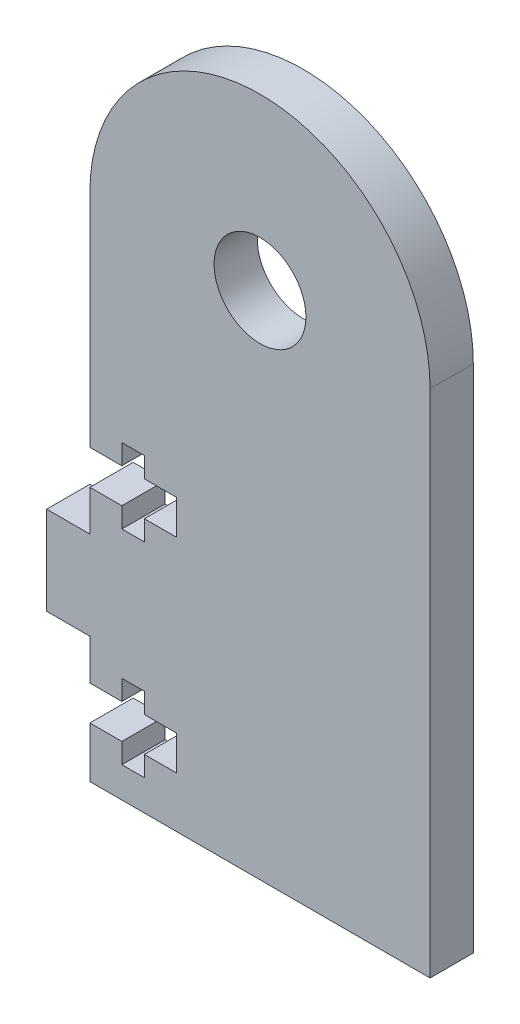
SolidWorks part; units mm, degrees
ref_plane "Front Plane" through (0, 0, 0) normal (0, 0, 1) x (1, 0, 0)
ref_plane "Top Plane" through (0, 0, 0) normal (0, 1, 0) x (1, 0, 0)
ref_plane "Right Plane" through (0, 0, 0) normal (1, 0, 0) x (0, 0, -1)
sketch "Sketch2" plane through (0, 0, 0) normal (0, 0, 1) x (1, 0, 0)
  line L0 (-25, 0) -> (25, 0) construction
  line L2 (-25, 0) -> (-25, -75)
  line L3 (-25, -75) -> (25, -75)
  line L4 (25, 0) -> (25, -75)
  arc A0 (25, 0) -> (-25, 0) centre (0, 0) ccw
  dimension "D1" = 50
  dimension "D2" = 75
extrude "Boss-Extrude1" add sketch "Sketch2" along normal blind 6.35
sketch "Sketch3" plane through (0, 0, 6.35) normal (0, 0, 1) x (1, 0, 0)
  line L0 (-25, -65) -> (-12.3, -65) construction
  line L1 (-12.3, -67.54) -> (-16.999, -67.54)
  line L2 (-25, -67.54) -> (-25, -62.46)
  line L3 (-12.3, -62.46) -> (-16.999, -62.46)
  line L4 (-20.301, -67.54) -> (-25, -67.54)
  line L5 (-20.301, -70.4991) -> (-20.301, -67.54)
  line L6 (-20.301, -70.4991) -> (-16.999, -70.4991)
  line L7 (-16.999, -70.4991) -> (-16.999, -67.54)
  line L8 (-20.301, -59.5009) -> (-16.999, -59.5009)
  line L9 (-20.301, -62.46) -> (-20.301, -59.5009)
  line L10 (-20.301, -62.46) -> (-25, -62.46)
  line L11 (-16.999, -62.46) -> (-16.999, -59.5009)
  line L12 (-12.3, -62.46) -> (-12.3, -67.54)
  line L13 (-25, -65) -> (-12.3, -65) construction
  line L14 (-25, 0) -> (-25, -75) construction
  line L15 (-25, -75) -> (25, -75) construction
  point P4 (-25, -65)
  dimension "D1" = 5.08
  dimension "D2" = 12.7
  dimension "D3" = 10
  dimension "D4" = 3.302
  dimension "D5" = 10.9982
extrude "Cut-Extrude1" cut sketch "Sketch3" against normal blind 6.35
pattern_linear "LPattern1" count 2 spacing 30 along (0, 1, 0) of "Cut-Extrude1"
sketch "Sketch4" plane through (0, 0, 6.35) normal (0, 0, 1) x (1, 0, 0)
  line L0 (-25, -37.54) -> (-25, -62.46) construction
  line L1 (-25, -43.5) -> (-31.35, -43.5)
  line L2 (-25, -43.5) -> (-25, -56.5)
  line L3 (-25, -56.5) -> (-31.35, -56.5)
  line L4 (-31.35, -43.5) -> (-31.35, -56.5)
  point P6 (-25, -50)
  dimension "D1" = 6.35
  dimension "D2" = 13
extrude "Boss-Extrude2" add sketch "Sketch4" against normal blind 6.35
sketch "Sketch5" plane through (0, 0, 6.35) normal (0, 0, 1) x (1, 0, 0)
  circle A0 centre (0, 0) radius 6.75
  dimension "D1" = 13.5
extrude "Cut-Extrude2" cut sketch "Sketch5" against normal through all
